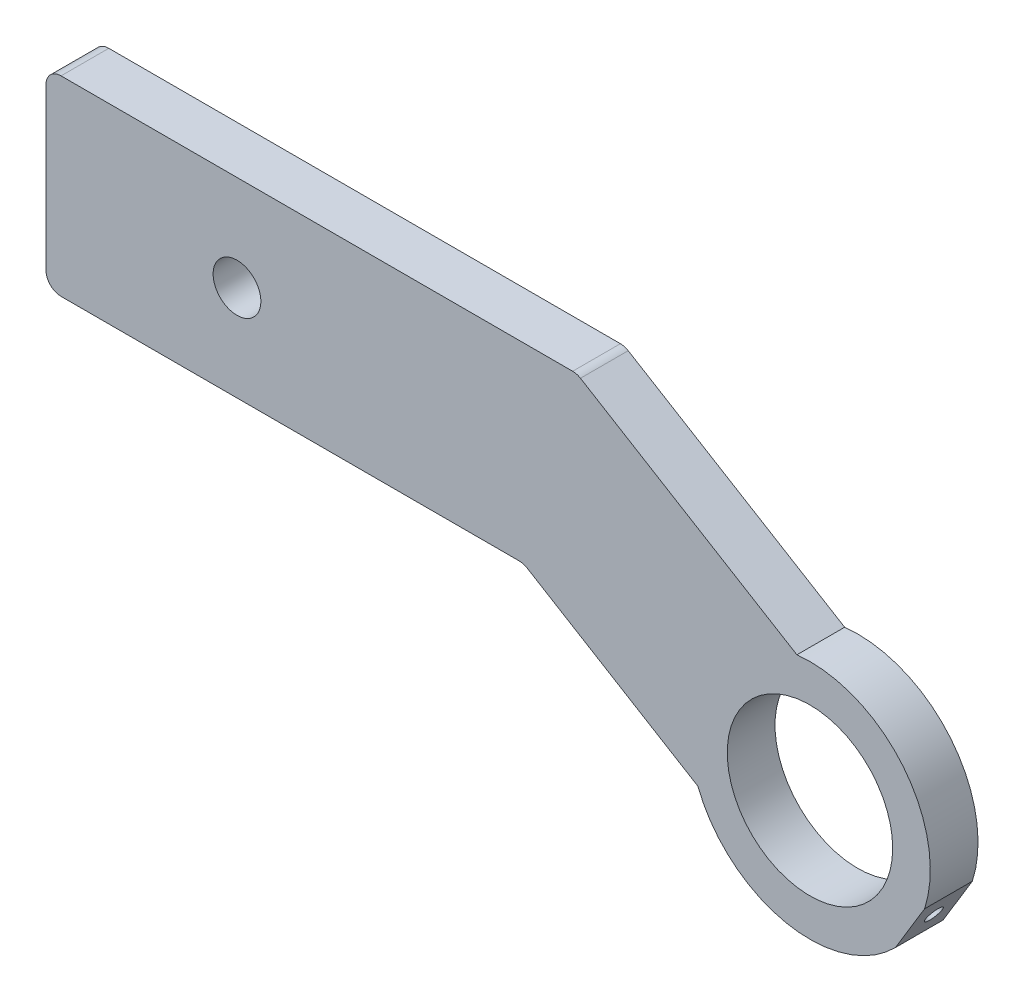
SolidWorks part; units mm, degrees
ref_plane "Front Plane" through (0, 0, 0) normal (0, 0, 1) x (1, 0, 0)
ref_plane "Top Plane" through (0, 0, 0) normal (0, 1, 0) x (1, 0, 0)
ref_plane "Right Plane" through (0, 0, 0) normal (1, 0, 0) x (0, 0, -1)
sketch "Sketch1" plane through (0, 0, 0) normal (0, 0, 1) x (1, 0, 0)
  line L0 (0, 0) -> (-25.4, 0) construction
  line L2 (-25.4, -12.7) -> (-25.4, 12.7)
  line L5 (82.7848, -10.0904) -> (69.6152, -31.8096) construction
  line L6 (38.1, -12.7) -> (61.2936, -26.7637) construction
  line L25 (45.1992, 12.7) -> (-25.4, 12.7)
  line L26 (38.1, -12.7) -> (-25.4, -12.7)
  line L27 (45.1992, 12.7) -> (74.4632, -5.0445)
  line L28 (76.2, -20.95) -> (110.4003, -41.6877) construction
  line L29 (91.4446, -25.8082) -> (87.5559, -32.2213)
  line L30 (38.1, -12.7) -> (61.2936, -26.7637)
  circle A0 centre (0, 0) radius 3.175
  circle A13 centre (76.2, -20.95) radius 11
  circle A14 centre (76.2, -20.95) radius 16 construction
  arc A15 (87.5559, -32.2213) -> (61.2936, -26.7637) centre (76.2, -20.95) cw
  arc A16 (74.4632, -5.0445) -> (91.4446, -25.8082) centre (76.2, -20.95) cw
  point P13 (89.5003, -29.0148)
  dimension "D4" = 6.35
  dimension "D7" = 5
  dimension "D8" = 25.4
  dimension "D10" = 7.5
  dimension "D5" = 76.2
  dimension "D6" = 20.95
  dimension "D9" = 22
  dimension "D2" = 38.1
  dimension "D3" = 25.4
  dimension "D13" = 25.4
extrude "Boss-Extrude1" add sketch "Sketch1" along normal blind 6.35
sketch "Sketch2" plane through (78.3036, -47.4802, 0) normal (0.8551, -0.5185, 0) x (0, 0, -1)
  line L0 (-6.35, 21.5949) -> (0, 21.5949) construction
  line L1 (-6.35, 17.8449) -> (-6.35, 25.3449) construction
  line L2 (0, 17.8449) -> (0, 25.3449) construction
  circle A0 centre (-3.175, 21.5949) radius 1.1303
  dimension "D1" = 2.2606
extrude "Cut-Extrude1" cut sketch "Sketch2" against normal up to next
sketch "Sketch3" plane through (0, 0, 0) normal (0, 0, 1) x (1, 0, 0)
  line L0 (-25.4, 0) -> (66.1438, 0) construction
  line L1 (-25.4, 12.7) -> (-25.4, -12.7) construction
  line L2 (74.4632, -5.0445) -> (45.1992, 12.7) construction
  line L4 (7.9375, -3.175) -> (33.3375, -3.175)
  line L5 (7.9375, -3.175) -> (7.9375, 3.175)
  line L6 (7.9375, 3.175) -> (33.3375, 3.175)
  line L7 (33.3375, -3.175) -> (33.3375, 3.175)
  line L8 (7.9375, -3.175) -> (33.3375, 3.175) construction
  line L9 (7.9375, 3.175) -> (33.3375, -3.175) construction
  line L10 (-19.05, -3.175) -> (-12.7, -3.175)
  line L11 (-19.05, -3.175) -> (-19.05, 3.175)
  line L12 (-19.05, 3.175) -> (-12.7, 3.175)
  line L13 (-12.7, -3.175) -> (-12.7, 3.175)
  line L14 (-19.05, -3.175) -> (-12.7, 3.175) construction
  line L15 (-19.05, 3.175) -> (-12.7, -3.175) construction
  point P7 (20.6375, 0)
  point P12 (-15.875, 0)
  dimension "D1" = 12.7
  dimension "D2" = 7.9375
  dimension "D3" = 25.4
  dimension "D4" = 6.35
  dimension "D5" = 6.35
extrude "Boss-Extrude2" add sketch "Sketch3" against normal blind 4.7625
fillet "Fillet3" radius 2 12 edges at (-25.4, -12.7, 3.175) (-25.4, 12.7, 3.175) (45.1992, 12.7, 3.175) (38.1, -12.7, 3.175) (-19.05, 3.175, -2.3813) (-12.7, 3.175, -2.3813) (-12.7, -3.175, -2.3813) (-19.05, -3.175, -2.3813) (7.9375, 3.175, -2.3813) (7.9375, -3.175, -2.3813) (33.3375, 3.175, -2.3813) (33.3375, -3.175, -2.3813)
